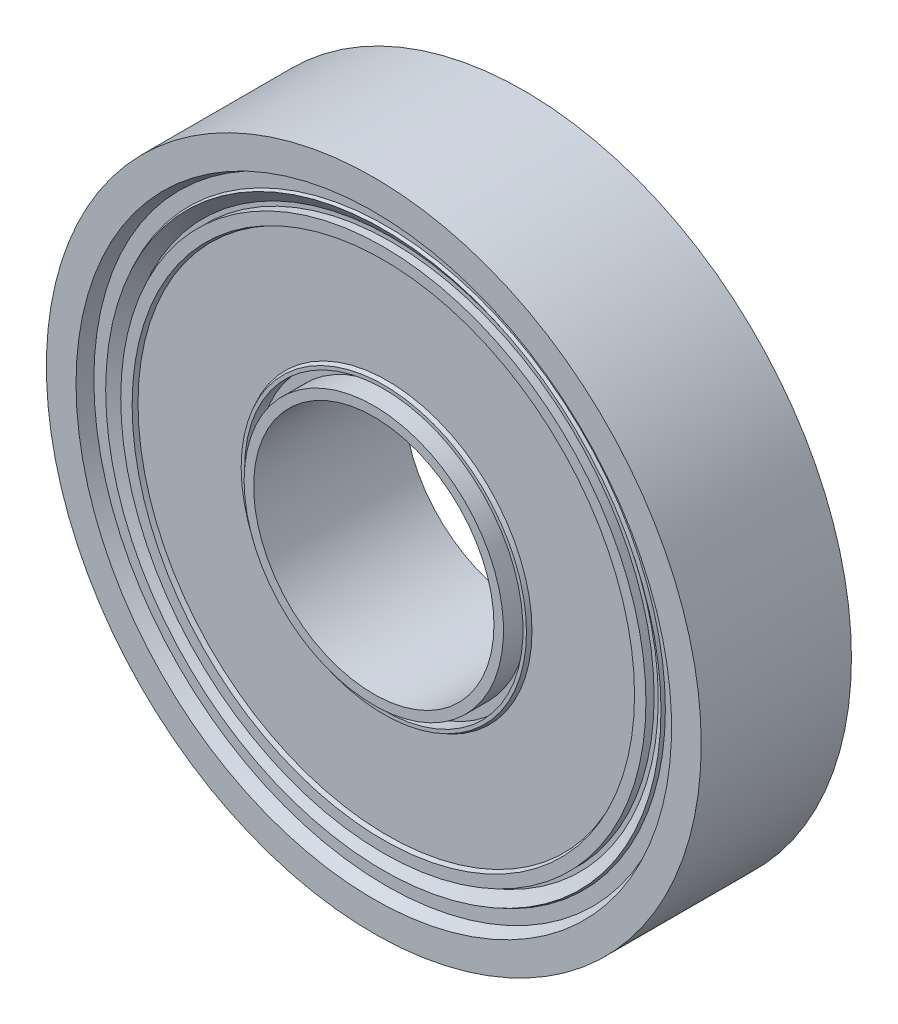
SolidWorks part; units mm, degrees
ref_plane "Front Plane" through (0, 0, 0) normal (0, 0, 1) x (1, 0, 0)
ref_plane "Top Plane" through (0, 0, 0) normal (0, 1, 0) x (1, 0, 0)
ref_plane "Right Plane" through (0, 0, 0) normal (1, 0, 0) x (0, 0, -1)
sketch "Sketch1" plane through (0, 0, 0) normal (0, 0, 1) x (1, 0, 0)
  circle A0 centre (0, 0) radius 4
  circle A1 centre (0, 0) radius 10.9
  dimension "D1" = 8
  dimension "D2" = 21.8
extrude "Boss-Extrude1" add sketch "Sketch1" along normal blind 5
ref_plane "Plane1" through (10.9, 0, 0) normal (1, 0, 0) x (0, 0, -1)
sketch "Sketch2" plane through (0, 0, 0) normal (0, 1, 0) x (1, 0, 0)
  line L0 (-10.9, -5) -> (-9.9129, -5)
  line L1 (-10.9, -5) -> (10.9, -5) construction
  line L2 (-9.9129, -5) -> (-9.733, -4.5869)
  line L3 (-9.733, -4.5869) -> (-9.2933, -4.5869)
  line L4 (-9.2933, -4.5869) -> (-9.2432, -4.6829)
  line L5 (-9.2432, -4.6829) -> (-8.8787, -4.4096)
  line L6 (-8.8787, -4.4096) -> (-8.7421, -4.4096)
  line L7 (-8.7421, -4.4096) -> (-8.7421, -4.6829)
  line L8 (-8.7421, -4.6829) -> (-8.3625, -4.6829)
  line L9 (-8.3625, -4.6829) -> (-8.303, -4.5462)
  line L10 (-8.303, -4.5462) -> (-4.8122, -4.5462)
  line L11 (-4.8122, -4.5462) -> (-4.7487, -4.6677)
  line L12 (-4.7487, -4.6677) -> (-4.6357, -4.6677)
  line L13 (-4.6357, -4.6677) -> (-4.6357, -4.2167)
  line L14 (-4.6357, -4.2167) -> (-4.3178, -4.2167)
  line L15 (-4, -4.2167) -> (-4, -5) construction
  line L16 (-4.3178, -4.2167) -> (-4.3178, -5)
  line L17 (-10.9, -5) -> (-10.9, -5.8092)
  line L18 (-10.9, -5.8092) -> (-6.3807, -5.7046)
  line L19 (-6.3807, -5.7046) -> (-4.3178, -5)
  line L20 (0, 0) -> (0, -3.0185) construction
  line L22 (-10.9, -2.5) -> (-8.8787, -2.5) construction
  line L24 (-4, -0.7833) -> (-4, 0) construction
  line L25 (-6.3807, 0.7046) -> (-4.3178, 0)
  line L26 (-10.9, 0.8092) -> (-6.3807, 0.7046)
  line L27 (-10.9, 0) -> (-10.9, 0.8092)
  line L28 (-4.3178, -0.7833) -> (-4.3178, 0)
  line L29 (-4.6357, -0.7833) -> (-4.3178, -0.7833)
  line L30 (-4.6357, -0.3323) -> (-4.6357, -0.7833)
  line L31 (-4.7487, -0.3323) -> (-4.6357, -0.3323)
  line L32 (-4.8122, -0.4538) -> (-4.7487, -0.3323)
  line L33 (-8.303, -0.4538) -> (-4.8122, -0.4538)
  line L34 (-8.3625, -0.3171) -> (-8.303, -0.4538)
  line L35 (-8.7421, -0.3171) -> (-8.3625, -0.3171)
  line L36 (-8.7421, -0.5904) -> (-8.7421, -0.3171)
  line L37 (-8.8787, -0.5904) -> (-8.7421, -0.5904)
  line L38 (-9.2432, -0.3171) -> (-8.8787, -0.5904)
  line L39 (-9.2933, -0.4131) -> (-9.2432, -0.3171)
  line L40 (-9.733, -0.4131) -> (-9.2933, -0.4131)
  line L41 (-9.9129, 0) -> (-9.733, -0.4131)
  line L42 (-10.9, 0) -> (-9.9129, 0)
  dimension "D1" = 4
revolve "Cut-Revolve1" cut sketch "Sketch2" angle 360 about L20
